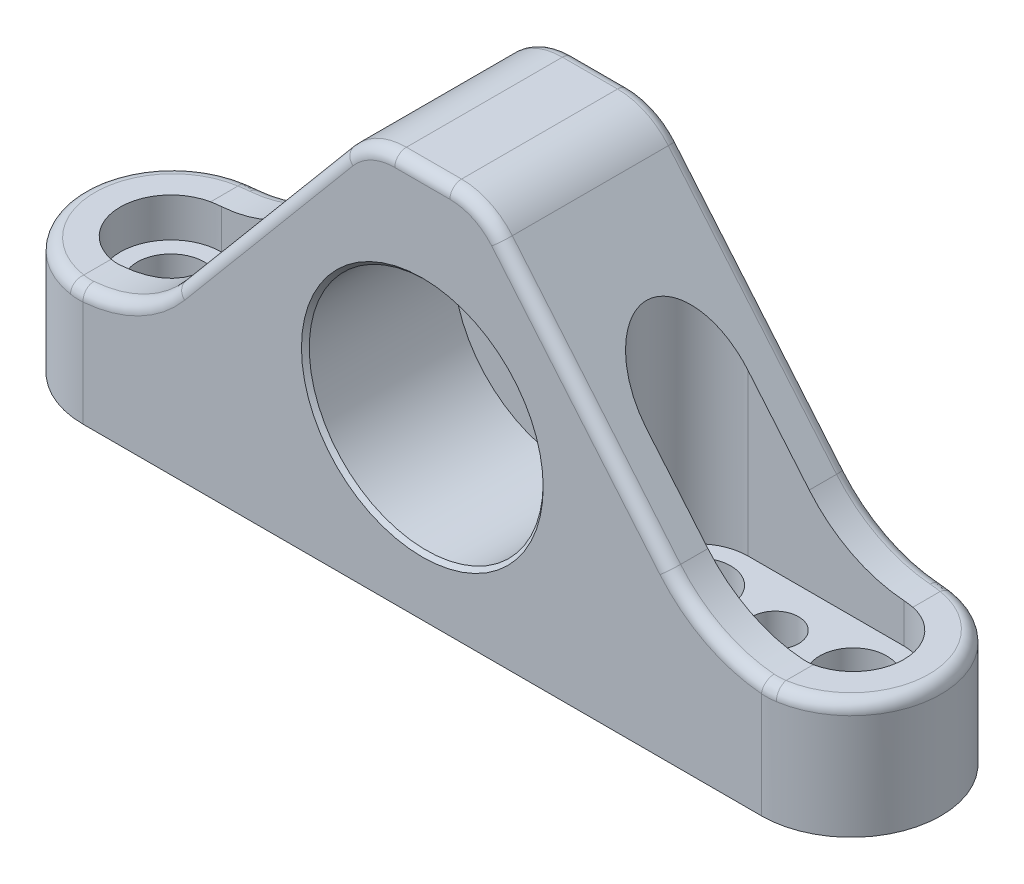
SolidWorks part; units mm, degrees
material "356.0-T6 Permanent Mold cast (SS)"
ref_plane "Front Plane" through (0, 0, 0) normal (0, 0, 1) x (1, 0, 0)
ref_plane "Top Plane" through (0, 0, 0) normal (0, 1, 0) x (1, 0, 0)
ref_plane "Right Plane" through (0, 0, 0) normal (1, 0, 0) x (0, 0, -1)
sketch "Sketch1" plane through (0, 0, 0) normal (0, 0, 1) x (1, 0, 0)
  line L0 (110, 0) -> (-110, 0)
  line L2 (110, 30) -> (110, 0)
  line L3 (110, 30) -> (73.737, 30)
  line L4 (73.737, 30) -> (15, 100)
  line L5 (0, 100) -> (0, 0) construction
  line L6 (15, 100) -> (-15, 100)
  line L7 (-73.737, 30) -> (-15, 100)
  line L8 (-110, 30) -> (-73.737, 30)
  line L9 (-110, 30) -> (-110, 0)
  point P4 (0, 0)
  dimension "D1" = 220
  dimension "D2" = 30
  dimension "D3" = 30
  dimension "D4" = 100
  dimension "D5" = 40
extrude "Boss-Extrude1" add sketch "Sketch1" along normal mid plane 46
sketch "Sketch2" plane through (0, 0, 0) normal (0, 1, 0) x (1, 0, 0)
  line L0 (87, 0) -> (-87, 0) construction
  line L1 (87, -23) -> (-87, -23)
  line L2 (87, 23) -> (-87, 23)
  line L4 (-110, 23) -> (110, 23) construction
  line L5 (110, -23) -> (110, 23) construction
  arc A0 (87, -23) -> (87, 23) centre (87, 0) ccw
  arc A1 (-87, 23) -> (-87, -23) centre (-87, 0) ccw
  point P2 (0, 0)
extrude "Cut-Extrude1" cut sketch "Sketch2" along normal through all flip side to cut
fillet "Fillet1" radius 35 2 edges at (73.737, 30, 0) (-73.737, 30, 0)
fillet "Fillet2" radius 17 2 edges at (15, 100, 0) (-15, 100, 0)
sketch "Sketch3" plane through (0, 0, 0) normal (0, 1, 0) x (1, 0, 0)
  line L0 (87.5, 0) -> (-87.5, 0) construction
  line L1 (-87.5, 0) -> (-47.5, 0) construction
  line L2 (-87.5, 13) -> (-47.5, 13)
  line L3 (-87.5, -13) -> (-47.5, -13)
  line L4 (87.5, 0) -> (47.5, 0) construction
  line L5 (87.5, -13) -> (47.5, -13)
  line L6 (87.5, 13) -> (47.5, 13)
  arc A2 (-87.5, 13) -> (-87.5, -13) centre (-87.5, 0) ccw
  arc A3 (-47.5, -13) -> (-47.5, 13) centre (-47.5, 0) ccw
  arc A4 (87.5, -13) -> (87.5, 13) centre (87.5, 0) ccw
  arc A5 (47.5, 13) -> (47.5, -13) centre (47.5, 0) ccw
  point P0 (-67.5, 0)
  point P4 (0, 0)
  point P11 (67.5, 0)
  dimension "D1" = 26
  dimension "D2" = 175
  dimension "D3" = 40
extrude "Cut-Extrude2" cut sketch "Sketch3" along normal through all from offset 20
sketch "Sketch4" plane through (0, 20, 0) normal (0, 1, 0) x (1, 0, 0)
  line L0 (87.5, 0) -> (47.5, 0) construction
  line L1 (-47.5, 0) -> (-87.5, 0) construction
  circle A0 centre (-87.5, 0) radius 8.6
  circle A1 centre (-47.5, 0) radius 8.6
  circle A2 centre (47.5, 0) radius 8.6
  circle A3 centre (87.5, 0) radius 8.6
  circle A4 centre (67.5, 0) radius 6
  circle A5 centre (-67.5, 0) radius 6
  dimension "D1" = 17.2
  dimension "D2" = 12
extrude "Cut-Extrude3" cut sketch "Sketch4" against normal through all
sketch "Sketch5" plane through (0, 0, 23) normal (0, 0, 1) x (1, 0, 0)
  line L0 (0, 45) -> (0, 0) construction
  circle A0 centre (0, 45) radius 30
  dimension "D1" = 60
  dimension "D2" = 45
extrude "Cut-Extrude4" cut sketch "Sketch5" against normal blind 38
sketch "Sketch6" plane through (0, 0, -23) normal (0, 0, -1) x (-1, 0, 0)
  line L0 (-20, 45) -> (20, 45) construction
  line L1 (0, 45) -> (0, 0) construction
  line L2 (87, 0) -> (-87, 0) construction
  circle A0 centre (20, 45) radius 4.5
  circle A1 centre (-20, 45) radius 4.5
  circle A2 centre (0, 45) radius 3.4
  dimension "D3" = 9
  dimension "D4" = 6.8
  dimension "D1" = 45
  dimension "D2" = 40
extrude "Cut-Extrude5" cut sketch "Sketch6" against normal through all
sketch "Sketch7" plane through (0, 0, -23) normal (0, 0, -1) x (-1, 0, 0)
  circle A0 centre (20, 45) radius 7.5
  circle A1 centre (-20, 45) radius 7.5
  dimension "D1" = 15
extrude "Cut-Extrude6" [suppressed] cut sketch "Sketch7" against normal blind 1
chamfer "Chamfer1" distance 1 angle 45 1 edges at (30, 45, 23)
chamfer "Chamfer2" [suppressed] distance 0.25 angle 45
fillet "Fillet3" radius 3 20 edges at (-14.2573, 98.4072, 23) (0, 100, 23) (14.2573, 98.4072, 23) (41.6709, 68.2149, 23) (73.8933, 33.9563, 23) (110, 30, 0) (73.8933, 33.9563, -23) (41.6709, 68.2149, -23) (14.2573, 98.4072, -23) (0, 100, -23) (-14.2573, 98.4072, -23) (-41.6709, 68.2149, -23) (-73.8933, 33.9563, -23) (-110, 30, 0) (-73.8933, 33.9563, 23) (-41.6709, 68.2149, 23)
